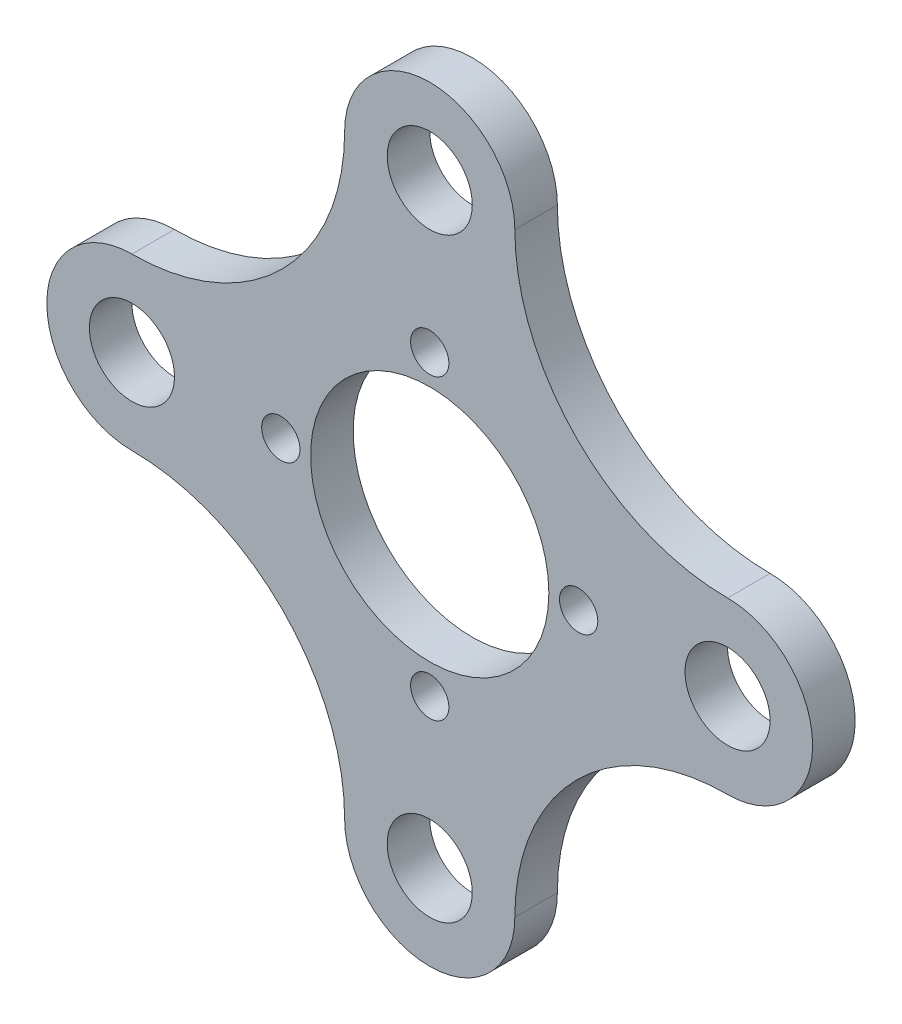
SolidWorks part; units mm, degrees
ref_plane "Płaszczyzna przednia" through (0, 0, 0) normal (0, 0, 1) x (1, 0, 0)
ref_plane "Płaszczyzna górna" through (0, 0, 0) normal (0, 1, 0) x (1, 0, 0)
ref_plane "Płaszczyzna prawa" through (0, 0, 0) normal (1, 0, 0) x (0, 0, -1)
sketch "Szkic1" plane through (0, 0, 0) normal (0, 0, 1) x (1, 0, 0)
  line L0 (0, 14) -> (0, 17.5)
  line L1 (14, 0) -> (17.5, 0)
  arc A0 (-17.3554, 2.2453) -> (-17.3554, -2.2453) centre (0, 0) ccw
  circle A1 centre (0, 17.5) radius 2.25
  circle A2 centre (17.5, 0) radius 2.25
  circle A3 centre (0, -17.5) radius 2.25
  circle A4 centre (-17.5, 0) radius 2.25
  circle A5 centre (0, 0) radius 14
  circle A6 centre (0, 0) radius 24
  arc A7 (2.2453, 17.3554) -> (-2.2453, 17.3554) centre (0, 0) ccw
  arc A8 (17.3554, -2.2453) -> (17.3554, 2.2453) centre (0, 0) ccw
  arc A9 (-2.2453, -17.3554) -> (2.2453, -17.3554) centre (0, 0) ccw
  circle A10 centre (0, 0) radius 17.5
  dimension "D1" = 28
  dimension "D2" = 35
  dimension "D3" = 48
  dimension "D4" = 4.5
extrude "Dodanie-wyciągnięcie1" add sketch "Szkic1" along normal blind 5 contours A1 A10 A4 A3 A2 L1 A5 L0 | A2 A10 A1 L0 A5 L1 | A6 A10 A2 A3 A4 A1
sketch "Szkic2" plane through (0, 0, 5) normal (0, 0, 1) x (1, 0, 0)
  line L0 (-10, -35) -> (-10, -20.1556)
  line L5 (35, 0) -> (35, -10)
  line L6 (35, -10) -> (20.1556, -10)
  line L7 (10, -35) -> (10, -20.1556)
  line L8 (-35, -10) -> (-20.1556, -10)
  line L9 (-10, 35) -> (-10, 20.1556)
  line L10 (-35, 10) -> (-20.1556, 10)
  line L11 (10, 20.1556) -> (10, 35)
  line L12 (20.1556, 10) -> (35, 10)
  circle A0 centre (0, 0) radius 22.5
  circle A1 centre (0, 35) radius 5
  circle A2 centre (0, 35) radius 10
  circle A3 centre (35, 0) radius 5
  circle A4 centre (35, 0) radius 10
  circle A5 centre (0, -35) radius 5
  circle A6 centre (0, -35) radius 10
  circle A7 centre (-35, 0) radius 5
  circle A8 centre (-35, 0) radius 10
  arc A9 (-35, -10) -> (-10, -35) centre (-35, -35) cw
  arc A10 (10, -35) -> (35, -10) centre (35, -35) cw
  arc A11 (35, 10) -> (10, 35) centre (35, 35) cw
  arc A12 (-10, 35) -> (-35, 10) centre (-35, 35) cw
  circle A13 centre (0, 0) radius 35
  circle M10 centre (0, 17.5) radius 2.25
  circle M11 centre (-17.5, 0) radius 2.25
  circle M12 centre (0, -17.5) radius 2.25
  circle M13 centre (17.5, 0) radius 2.25
  circle M14 centre (0, 0) radius 14
  circle M15 centre (0, 0) radius 24
  dimension "D2" = 20
  dimension "D3" = 45
  dimension "D7" = 10
  dimension "D1" = 35
extrude "Dodanie-wyciągnięcie2" add sketch "Szkic2" against normal blind 5 contours A13 A8 A7 | A8 A13 A7 | L10 A13 A8 L8 M15 | L9 A13 A12 L10 M15 | L11 A13 A2 L9 M15 | A2 A13 A1 | A13 A2 A1 | A13 A6 A5 | A13 A3 L5 A4 | A3 A13 A4 | A4 A13 L12 L6 M15 | L12 A13 A11 L11 M15 | L7 A13 A10 L6 M15 | A6 A13 A5 | L8 A13 A9 L0 M15 | L0 A13 A6 L7 M15 | A0 L8 L0 M15 | A0 L0 L7 M15 | A0 M11 M13 M14 M12 M10 | A0 L7 L6 M15 | A0 L6 L12 M15 | A0 L12 L11 M15 | A0 L11 L9 M15 | A0 L9 L10 M15 | A0 L10 L8 M15 | A13 A4 L5 A3 | A13 L6 A4 | A13 A10 L6 | A13 A4 L12 | A13 L12 A11 | A13 A11 L11 | A13 L11 A2 | A13 L9 A12 | A13 A2 L9 | A13 L10 A8 | A13 A12 L10 | A13 A8 L8 | A13 L8 A9 | A13 L0 A6 | A13 A9 L0 | A13 A6 L7 | A13 L7 A10
